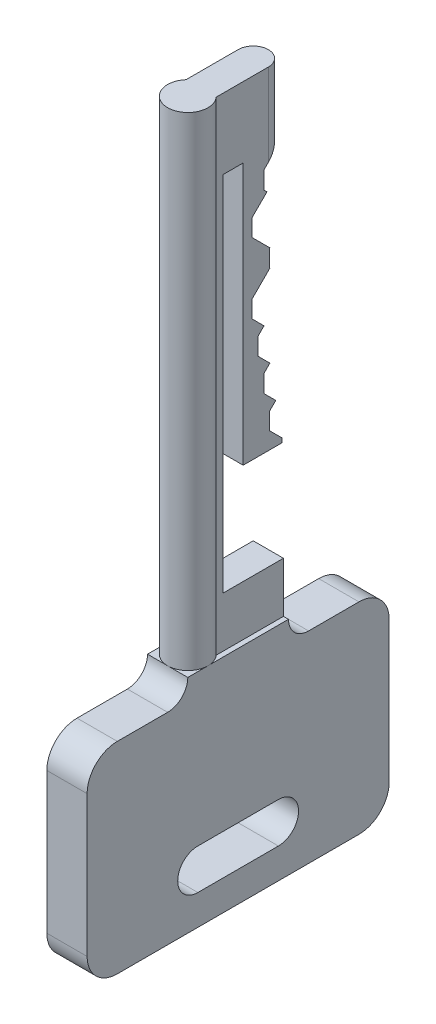
SolidWorks part; units mm, degrees
ref_plane "Front Plane" through (0, 0, 0) normal (0, 0, 1) x (1, 0, 0)
ref_plane "Top Plane" through (0, 0, 0) normal (0, 1, 0) x (1, 0, 0)
ref_plane "Right Plane" through (0, 0, 0) normal (1, 0, 0) x (0, 0, -1)
sketch "Sketch1" plane through (0, 108.422, -620.3475) normal (1, 0, 0) x (0, 0, -1)
  line L2 (-620.3475, -60.422) -> (-620.3475, -108.422)
  line L5 (-612.3475, -60.422) -> (-612.3475, -64.422)
  line L8 (-612.3475, -60.422) -> (-620.3475, -60.422)
  line L12 (-618.3475, -48.422) -> (-616.3475, -48.422) construction
  line L13 (-612.3475, -93.422) -> (-612.3475, -103.422) construction
  line L15 (-620.3475, -17.422) -> (-620.3475, -43.422) construction
  line L18 (-620.3475, -108.422) -> (-612.3475, -108.422)
  line L19 (-612.3475, -108.422) -> (-612.3475, -103.422)
  line L20 (-612.3475, -103.422) -> (-618.3475, -103.422)
  line L22 (-616.3475, -93.422) -> (-616.3475, -67.422)
  line L23 (-616.3475, -67.422) -> (-618.3475, -67.422)
  line L24 (-618.3475, -67.422) -> (-618.3475, -103.422)
  line L25 (-616.3475, -93.422) -> (-612.3475, -93.422)
  line L26 (-612.3475, -64.422) -> (-612.3475, -93.422)
  line L28 (-612.4894, -43.422) -> (-612.4894, -14.422) construction
  line L29 (-619.2295, -10.422) -> (-619.2295, -14.422) construction
  line L32 (-618.3475, -67.422) -> (-620.3475, -67.422) construction
  line L33 (-620.3475, -48.422) -> (-618.3475, -48.422) construction
  line L35 (-620.3475, -10.422) -> (-612.3475, -10.422) construction
  line L41 (-620.3475, -43.422) -> (-620.3475, -53.422) construction
  dimension "D2" = 5
extrude "Boss-Extrude2" add sketch "Sketch1" along normal up to surface (1.5 mm away) and the other way up to surface (1.5 mm away)
sketch "Sketch2" plane through (0, 48, 0) normal (0, 1, 0) x (1, 0, 0)
  circle A0 centre (0, 0) radius 2
  arc A3 (-1.5, 1.3229) -> (1.5, 1.3229) centre (0, 0) ccw construction
extrude "Boss-Extrude3" add sketch "Sketch2" against normal up to surface (48 mm away) up to face at (0, 0, -4)
sketch "Sketch3" plane through (-1.5, 0, 0) normal (-1, 0, 0) x (0, 0, 1)
  line L0 (-8, 15) -> (-8, 16.0395) construction
  line L1 (0, 67.5) -> (0, 66.0395) construction
  line L2 (-9.4605, 21) -> (-9.4605, 17.5) construction
  line L3 (-8, 16.0395) -> (-8, 17.5) construction
  line L4 (0, 71) -> (0, 67.5) construction
  line L5 (-8, 18.9605) -> (-8, 19.5395) construction
  line L6 (-8, 19.5395) -> (-8, 21) construction
  line L8 (-8, 15.5198) -> (-6.047, 15.5198) construction
  line L9 (-8, 15.857) -> (-5.4628, 15.857) construction
  line L10 (-8, 16.1943) -> (-4.8786, 16.1943) construction
  line L11 (-8, 15.1825) -> (-6.6312, 15.1825) construction
  line L12 (-8, 22.4605) -> (-8, 23.0395) construction
  line L13 (-8, 25.9605) -> (-8, 26.5395) construction
  line L14 (-8, 29.4605) -> (-8, 30.0395) construction
  line L15 (-8, 32.9605) -> (-8, 33.5395) construction
  line L16 (-8, 36.4605) -> (-8, 37.0395) construction
  line L17 (-6.6312, 15.1825) -> (-6.6312, 38.5) construction
  line L18 (-4.8786, 16.1943) -> (-4.8786, 38.5) construction
  line L19 (-6.047, 15.5198) -> (-6.047, 38.5) construction
  line L20 (-8, 38.5) -> (-4.8786, 38.5) construction
  line L21 (-6.6312, 15.1825) -> (-4.8786, 16.1943) construction
  line L22 (-5.4628, 15.857) -> (-5.4628, 38.5) construction
  line L23 (-8, 17.5) -> (-4.8786, 17.5) construction
  line L24 (-8, 21) -> (-4.8786, 21) construction
  line L25 (-8, 24.5) -> (-4.8786, 24.5) construction
  line L26 (-8, 28) -> (-4.8786, 28) construction
  line L27 (-8, 31.5) -> (-4.8786, 31.5) construction
  line L28 (-8, 35) -> (-4.8786, 35) construction
  line L29 (-8, 15) -> (-8, 48) construction
  line L30 (0, 66.0395) -> (0, 65) construction
  circle A0 centre (-8, 17.5) radius 1.4605 construction
  circle A1 centre (-8, 21) radius 1.4605 construction
  circle A2 centre (-8, 24.5) radius 1.4605 construction
  circle A3 centre (-8, 28) radius 1.4605 construction
  circle A4 centre (-8, 31.5) radius 1.4605 construction
  circle A5 centre (-8, 35) radius 1.4605 construction
  circle A6 centre (-8, 38.5) radius 1.4605 construction
  point P15 (-9.8826, 17.5)
  point P47 (0, 0)
  point P51 (-8, 15)
  dimension "D1" = 1.953
  dimension "D2" = 1.3688
  dimension "D3" = 2.5372
  dimension "D4" = 3.1214
  dimension "D5" = 150
sketch "Sketch4" plane through (-1.5, 0, 0) normal (-1, 0, 0) x (0, 0, 1)
  line L0 (-8, 0) -> (2, 0)
  line L1 (-10, -2) -> (-15, -2)
  line L2 (-18, -5) -> (-18, -19)
  line L3 (-15, -22) -> (9, -22)
  line L4 (-3, 0) -> (-3, -22) construction
  line L5 (-8, 0) -> (-8, 5) construction
  line L6 (12, -5) -> (12, -19)
  line L7 (4, -2) -> (9, -2)
  line L8 (-7, -15) -> (1, -15)
  line L9 (-7, -19) -> (1, -19)
  arc A0 (-8, 0) -> (-10, -2) centre (-10, 0) cw
  arc A1 (-15, -2) -> (-18, -5) centre (-15, -5) ccw
  arc A2 (-18, -19) -> (-15, -22) centre (-15, -19) ccw
  arc A3 (12, -19) -> (9, -22) centre (9, -19) cw
  arc A4 (9, -2) -> (12, -5) centre (9, -5) cw
  arc A5 (2, 0) -> (4, -2) centre (4, 0) ccw
  arc A6 (-7, -15) -> (-7, -19) centre (-7, -17) ccw
  arc A7 (1, -15) -> (1, -19) centre (1, -17) cw
  point P30 (-3, -15)
  point P32 (-3, -19)
  dimension "D1" = 2
  dimension "D3" = 3
  dimension "D5" = 4
  dimension "D2" = 15
  dimension "D4" = 20
  dimension "D6" = 4
  dimension "D7" = 3
extrude "Boss-Extrude4" add sketch "Sketch4" along normal through all and the other way through all
sketch "Sketch6" plane through (-1.5, 0, 0) normal (-1, 0, 0) x (0, 0, 1)
  line L0 (-6.6312, 18.3509) -> (-6.6312, 16.6491)
  line L1 (-6.6312, 18.3509) -> (-7.2382, 18.9579)
  line L2 (-6.047, 20.1491) -> (-7.2382, 18.9579)
  line L3 (-6.047, 21.8509) -> (-6.654, 22.4579)
  line L4 (-8, 17.5) -> (-4.8786, 17.5) construction
  line L5 (-6.6312, 15.1825) -> (-6.6312, 38.5) construction
  line L6 (-6.047, 21.8509) -> (-6.047, 20.1491)
  line L7 (-8, 21) -> (-4.8786, 21) construction
  line L8 (-6.047, 15.5198) -> (-6.047, 38.5) construction
  line L9 (-5.4628, 25.3509) -> (-5.4628, 23.6491)
  line L10 (-8, 24.5) -> (-4.8786, 24.5) construction
  line L11 (-5.4628, 15.857) -> (-5.4628, 38.5) construction
  line L12 (-4.8786, 28.8509) -> (-4.8786, 27.1491)
  line L13 (-6.654, 22.4579) -> (-5.4628, 23.6491)
  line L14 (-6.6312, 32.3509) -> (-6.6312, 30.6491)
  line L15 (-8, 31.5) -> (-4.8786, 31.5) construction
  line L16 (-4.8786, 35.8509) -> (-4.8786, 34.1491)
  line L17 (-4.8786, 16.1943) -> (-4.8786, 38.5) construction
  line L18 (-6.047, 39.3509) -> (-6.047, 37.6491)
  line L19 (-5.4628, 25.3509) -> (-6.0698, 25.9579)
  line L20 (-6.0698, 25.9579) -> (-4.8786, 27.1491)
  line L21 (-4.8786, 28.8509) -> (-6.654, 30.6263)
  line L22 (-6.654, 30.6263) -> (-6.6312, 30.6491)
  line L23 (-6.6312, 32.3509) -> (-6.654, 32.3737)
  line L24 (-6.654, 32.3737) -> (-4.8786, 34.1491)
  line L25 (-6.047, 39.3509) -> (-8.2803, 41.5842)
  line L28 (-6.6312, 16.6491) -> (-8.2803, 15)
  line L29 (-4.8786, 35.8509) -> (-6.3619, 37.3342)
  line L31 (-6.3619, 37.3342) -> (-6.047, 37.6491)
  line L32 (-8.2803, 15) -> (-10.2803, 15)
  line L33 (-10.2803, 15) -> (-10.2803, 41.5842)
  line L34 (-10.2803, 41.5842) -> (-8.2803, 41.5842)
  line L35 (-4, 15) -> (-8, 15) construction
  point P3 (-6.6312, 17.5)
  point P10 (-6.047, 21)
  point P17 (-5.4628, 24.5)
  point P24 (-4.8786, 28)
  point P28 (-6.6312, 31.5)
  point P33 (-4.8786, 35)
  point P39 (-6.047, 38.5)
  dimension "D1" = 1.7018
  dimension "D2" = 45
  dimension "D3" = 45
  dimension "D4" = 135
  dimension "D5" = 2
extrude "Cut-Extrude1" cut sketch "Sketch6" against normal up to surface (3 mm away) up to face at (1.5, 21.8, -4.6646)
sketch "Sketch7" plane through (0, 15, 0) normal (0, -1, 0) x (1, 0, 0)
  line L1 (1.5, -8) -> (-1.5, -8) construction
  line L2 (0, -6.6312) -> (-1.5, -5.1312)
  line L3 (-1.5, -4) -> (-1.5, -8) construction
  line L4 (-1.5, -5.1312) -> (-1.5, -8)
  line L5 (-1.5, -8) -> (0, -8)
  line L7 (0, -8) -> (0, -6.6312)
  dimension "D1" = 45
  dimension "D2" = 1.3688
extrude "Cut-Extrude2" cut sketch "Sketch7" against normal up to vertex (26.3039 mm away) up to point (-1.5, 41.3039, -8)
fillet "Fillet1" radius 1 1 edges at (0, 41.3039, -7.3156)
sketch "Sketch9" plane through (0, 48, 0) normal (0, 1, 0) x (1, 0, 0)
  line L0 (1.5, 8) -> (-1.5, 8) construction
  line L3 (1.5, 8) -> (1.5, 6.5)
  line L4 (1.5, 8) -> (0, 8)
  line L7 (1.5, 6.5) -> (0, 6.5) construction
  line L8 (1.5, 8) -> (1.5, 1.3229) construction
  line L9 (-1.5, 8) -> (-1.5, 6.6312) construction
  line L10 (-1.5, 6.5) -> (-1.5, 8)
  line L11 (-1.5, 8) -> (0, 8)
  arc A1 (1.5, 6.5) -> (0, 8) centre (0, 6.5) ccw
  arc A2 (0, 8) -> (-1.5, 6.5) centre (0, 6.5) ccw
extrude "Cut-Extrude4" cut sketch "Sketch9" against normal up to surface (8.1961 mm away) contours A2 L10 L11 | A1 L3 L4
sketch "Sketch10" plane through (0, 15, 0) normal (0, 1, 0) x (1, 0, 0)
  line L0 (-1.5, 1.3229) -> (1.5, 1.3229) construction
  line L1 (-1.5, 1.3229) -> (-1.5, 8) construction
  line L2 (-1.5, 8) -> (1.5, 8)
  line L3 (1.5, 1.3229) -> (1.5, 8) construction
  line L4 (-1.5, 7.8581) -> (1.5, 7.8581)
  line L5 (-1.5, 8) -> (-1.5, 7.8581)
  line L6 (1.5, 8) -> (1.5, 7.8581)
  arc A0 (1.5, 7.8581) -> (-1.5, 7.8581) centre (0, 0) ccw construction
  arc A1 (1.5, 6.5) -> (-1.5, 6.5) centre (0, 6.5) ccw construction
  point P6 (0, 0)
  point P7 (0, 8)
extrude "Cut-Extrude5" cut sketch "Sketch10" along normal up to surface (0.2803 mm away)
